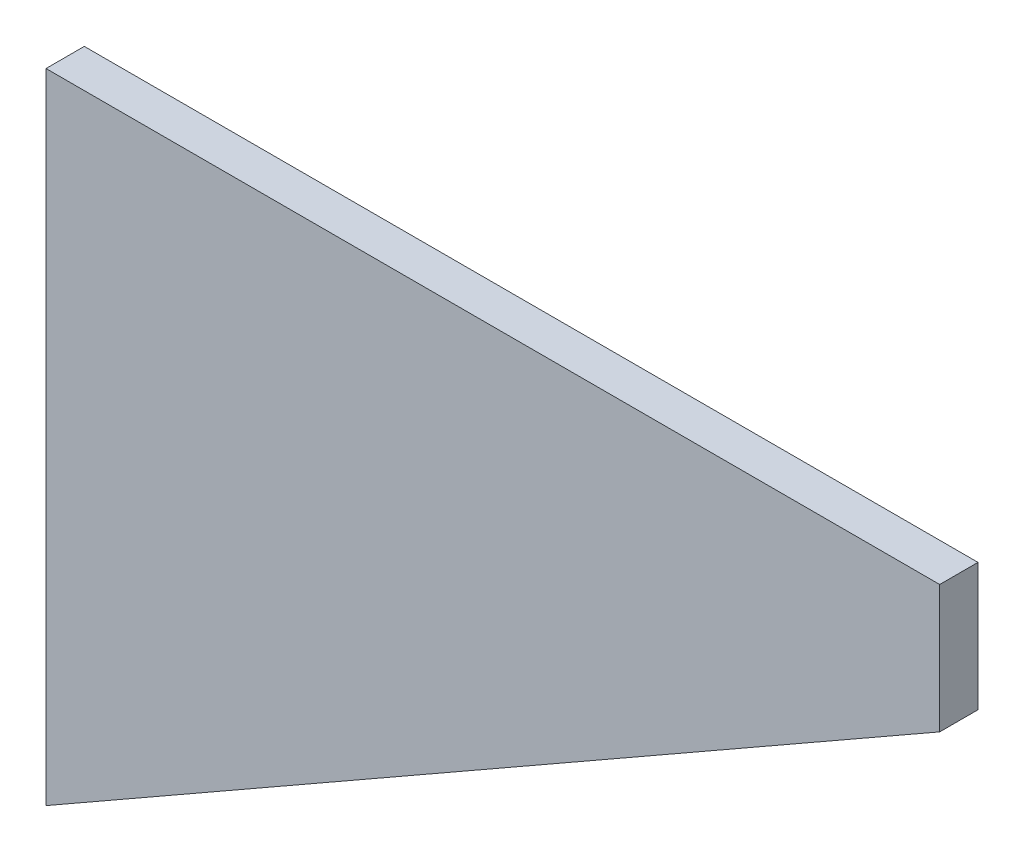
SolidWorks part; units mm, degrees
ref_plane "前视基准面" through (0, 0, 0) normal (0, 0, 1) x (1, 0, 0)
ref_plane "上视基准面" through (0, 0, 0) normal (0, 1, 0) x (1, 0, 0)
ref_plane "右视基准面" through (0, 0, 0) normal (1, 0, 0) x (0, 0, -1)
sketch "草图1" plane through (0, 0, 0) normal (0, 0, 1) x (1, 0, 0)
  line L0 (0, 0) -> (0, 100)
  line L1 (0, 100) -> (140, 100)
  line L2 (140, 100) -> (140, 80)
  line L4 (140, 80) -> (0, 0)
  dimension "D1" = 140
  dimension "D2" = 100
  dimension "D3" = 20
extrude "凸台-拉伸1" add sketch "草图1" along normal blind 6
